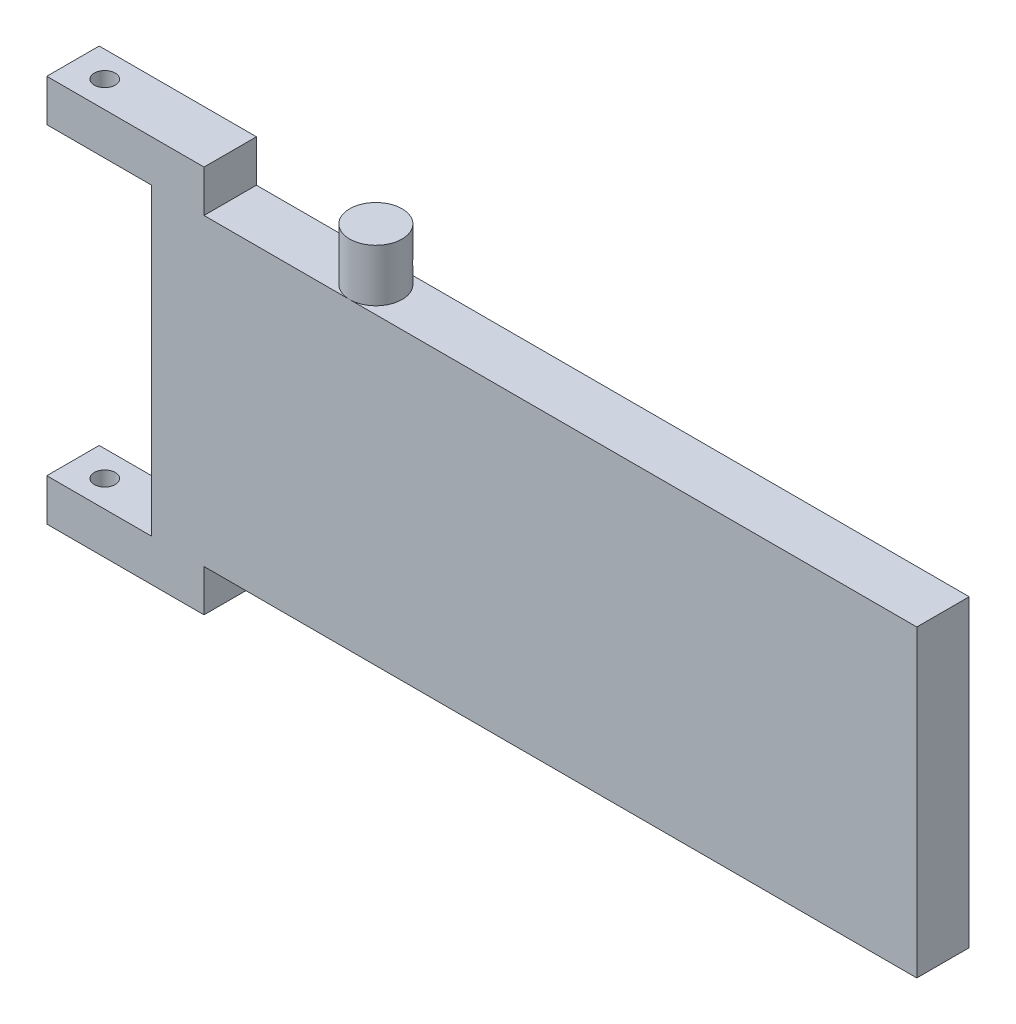
SolidWorks part; units mm, degrees
material "Copper"
ref_plane "Front Plane" through (0, 0, 0) normal (0, 0, 1) x (1, 0, 0)
ref_plane "Top Plane" through (0, 0, 0) normal (0, 1, 0) x (1, 0, 0)
ref_plane "Right Plane" through (0, 0, 0) normal (1, 0, 0) x (0, 0, -1)
sketch "Sketch1" plane through (0, 0, 0) normal (0, 0, 1) x (1, 0, 0)
  line L1 (0, 0) -> (73, 0)
  line L2 (0, 0) -> (0, 29)
  line L3 (0, 29) -> (73, 29)
  line L4 (73, 0) -> (73, 29)
  line L5 (5, 29) -> (-10, 29)
  line L6 (5, 29) -> (5, 33)
  line L7 (5, 33) -> (-10, 33)
  line L8 (-10, 29) -> (-10, 33)
  line L9 (5, 0) -> (-10, 0)
  line L10 (5, 0) -> (5, -4)
  line L11 (5, -4) -> (-10, -4)
  line L12 (-10, 0) -> (-10, -4)
  dimension "D1" = 73
  dimension "D2" = 29
  dimension "D3" = 5
  dimension "D4" = 5
  dimension "D5" = 15
  dimension "D6" = 4
extrude "Boss-Extrude1" add sketch "Sketch1" along normal blind 5 contours L1 L4 L3 L2 | L8 L5 L3 L6 L7 | L9 L12 L11 L10 L1
sketch "Sketch2" plane through (0, 33, 0) normal (0, 1, 0) x (1, 0, 0)
  line L0 (-10, -5) -> (-10, 0) construction
  circle A0 centre (-7, -2.4694) radius 1
  dimension "D1" = 3
  dimension "D2" = 2
extrude "Cut-Extrude1" cut sketch "Sketch2" against normal blind 35
sketch "Sketch3" plane through (0, 0, 0) normal (0, 0, -1) x (-1, 0, 0)
  line L0 (-5, 29) -> (-73, 29) construction
  line L1 (-38, 23) -> (-34, 23)
  line L2 (-38, 23) -> (-38, 17)
  line L3 (-38, 17) -> (-34, 17)
  line L4 (-34, 23) -> (-34, 17)
  line L6 (-73, 0) -> (-73, 29) construction
  dimension "D1" = 6
  dimension "D2" = 4
  dimension "D3" = 6
  dimension "D4" = 35
extrude "Boss-Extrude2" add sketch "Sketch3" along normal blind 5
sketch "Sketch4" plane through (38, 0, 0) normal (1, 0, 0) x (0, 0, -1)
  line L0 (0, 23) -> (0, 17) construction
  line L1 (0, 21) -> (3, 21)
  line L2 (0, 21) -> (0, 19)
  line L3 (0, 19) -> (3, 19)
  line L4 (3, 21) -> (3, 19)
  line L5 (5, 23) -> (0, 23) construction
  line L6 (5, 17) -> (0, 17) construction
  line L7 (5, 23) -> (5, 17) construction
  dimension "D1" = 2
  dimension "D2" = 2
  dimension "D3" = 2
extrude "Cut-Extrude2" cut sketch "Sketch4" against normal blind 10
sketch "Sketch5" plane through (0, 29, 0) normal (0, 1, 0) x (1, 0, 0)
  line L0 (5, -2.5) -> (18.895, -2.5) construction
  line L1 (5, -5) -> (5, 0) construction
  line L2 (5, 0) -> (73, 0) construction
  circle A0 centre (18.895, -2.5) radius 2.5
extrude "Boss-Extrude3" add sketch "Sketch5" along normal blind 5 contours A0
sketch "Sketch6" plane through (5, 0, 0) normal (1, 0, 0) x (0, 0, -1)
  line L0 (0, 33) -> (-1, 31)
  line L1 (-1, 31) -> (0, 29)
  line L2 (0, 29) -> (0, 33)
  line L3 (-1, 31) -> (0, 31) construction
  dimension "D1" = 1
extrude "Cut-Extrude3" cut sketch "Sketch6" along normal blind 25
fillet "Fillet1" radius 1 2 edges at (34, 20, -3) (38, 20, -3)
